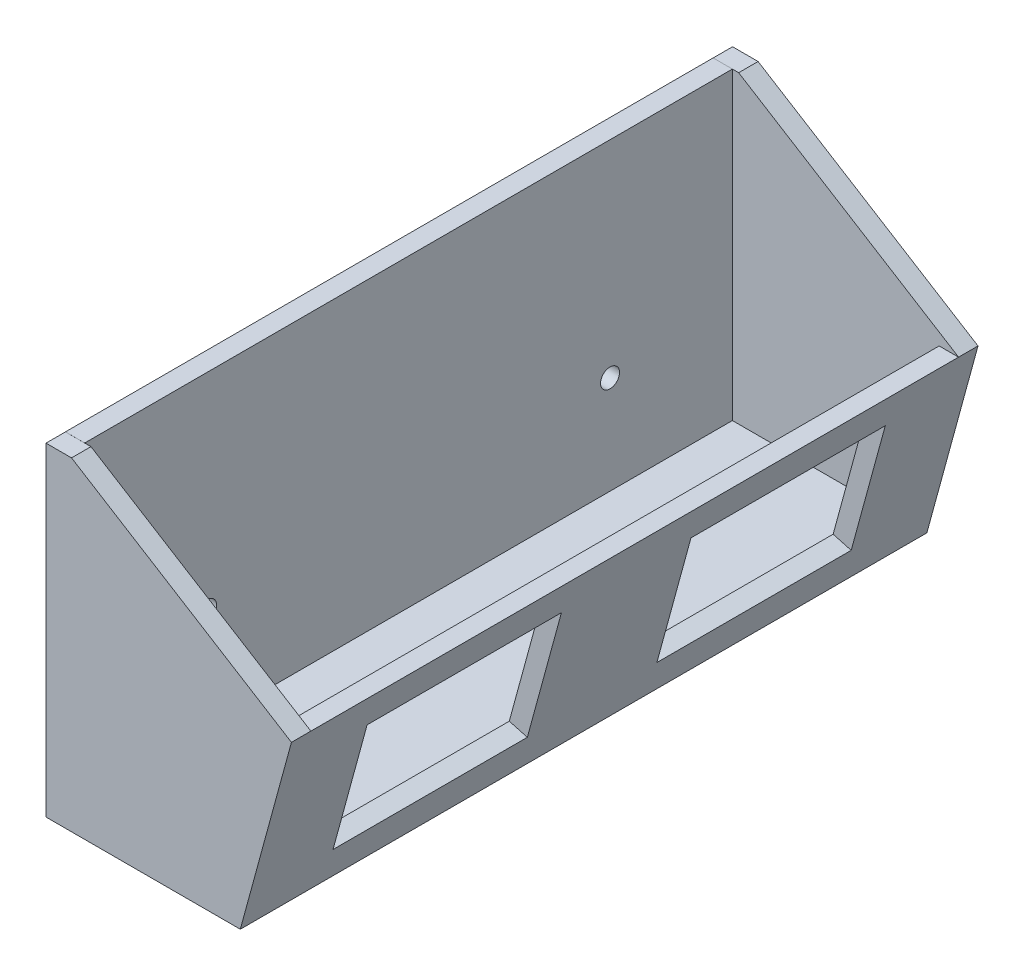
SolidWorks part; units mm, degrees
ref_plane "Front Plane" through (0, 0, 0) normal (0, 0, 1) x (1, 0, 0)
ref_plane "Top Plane" through (0, 0, 0) normal (0, 1, 0) x (1, 0, 0)
ref_plane "Right Plane" through (0, 0, 0) normal (1, 0, 0) x (0, 0, -1)
sketch "Esquisse2" plane through (0, 0, 0) normal (0, 0, 1) x (1, 0, 0)
  line L0 (0, 0) -> (0, 50)
  line L1 (0, 50) -> (3.9428, 50)
  line L2 (37.8943, 28.9427) -> (30, 0)
  line L3 (30, 0) -> (0, 0)
  line L4 (3.9428, 50) -> (37.8943, 28.9427)
  dimension "D1" = 50
  dimension "D2" = 30
  dimension "D3" = 30
  dimension "D4" = 105.257
extrude "Boss.-Extru.1" add sketch "Esquisse2" along normal blind 3
sketch "Esquisse4" plane through (0, 0, 3) normal (0, 0, 1) x (1, 0, 0)
  line L0 (0, 0) -> (0, 3.0061)
  line L1 (0, 50) -> (0, 0) construction
  line L2 (0, 3.0061) -> (30.8199, 3.0061)
  line L3 (30, 0) -> (37.8943, 28.9427) construction
  line L4 (30.8199, 3.0061) -> (30, 0)
  line L5 (30, 0) -> (0, 0)
extrude "Boss.-Extru.2" add sketch "Esquisse4" along normal blind 100
pattern_linear "Répétition linéaire1" count 2 spacing 103 along (0, 0, 1) of "Boss.-Extru.1"
sketch "Esquisse5" plane through (0, 3.0061, 0) normal (0, 1, 0) x (1, 0, 0)
  line L0 (30.8199, -103) -> (0, -103) construction
  line L1 (0, -3) -> (2.9757, -3)
  line L2 (0, -3) -> (0, -103)
  line L3 (0, -103) -> (2.9757, -103)
  line L4 (2.9757, -3) -> (2.9757, -103)
extrude "Boss.-Extru.3" add sketch "Esquisse5" along normal blind 47
sketch "Esquisse6" plane through (0, 3.0061, 0) normal (0, 1, 0) x (1, 0, 0)
  line L0 (30.8199, -103) -> (2.9757, -103) construction
  line L1 (30.8199, -3) -> (27.8243, -3)
  line L2 (30.8199, -3) -> (30.8199, -103)
  line L3 (30.8199, -103) -> (27.8243, -103)
  line L4 (27.8243, -3) -> (27.8243, -103)
sweep "Balayage1" add profiles "Esquisse6" path edge at (34.3571, 15.9744, 103)
sketch "Esquisse7" plane through (27.9227, -7.6161, 0) normal (0.9648, -0.2631, 0) x (0, 0, -1)
  line L0 (-53, 37.8943) -> (-53, 7.8943) construction
  line L1 (-93, 32.8943) -> (-63, 32.8943)
  line L2 (-93, 32.8943) -> (-93, 12.8943)
  line L3 (-93, 12.8943) -> (-63, 12.8943)
  line L4 (-63, 32.8943) -> (-63, 12.8943)
  line L5 (-103, 37.8943) -> (-3, 37.8943) construction
  line L6 (-106, 7.8943) -> (0, 7.8943) construction
  line L7 (-106, 22.8943) -> (0, 22.8943) construction
  line L8 (-106, 7.8943) -> (-106, 37.8943) construction
  line L9 (0, 7.8943) -> (0, 37.8943) construction
  point P16 (-93, 22.8943)
  dimension "D1" = 20
  dimension "D2" = 30
  dimension "D3" = 10
extrude "Enlèv. mat.-Extru.1" cut sketch "Esquisse7" against normal up to next
sketch "Esquisse8" plane through (27.9227, -7.6161, 0) normal (0.9648, -0.2631, 0) x (0, 0, -1)
  line L0 (-53, 37.8943) -> (-53, 7.8943) construction
  line L1 (-103, 37.8943) -> (-3, 37.8943) construction
  line L2 (-106, 7.8943) -> (0, 7.8943) construction
ref_plane "Plan3" through (0, 0, 53) normal (0, 0, 1) x (-0.2631, -0.9648, 0)
mirror "Symétrie1" about plane through (0, 0, 53) normal (0, 0, 1) of "Enlèv. mat.-Extru.1"
sketch "Esquisse9" plane through (2.9757, 0, 0) normal (1, 0, 0) x (0, 0, -1)
  circle A0 centre (-84.1079, 18.1575) radius 1.4621
  point P2 (-84.1079, 18.1575)
extrude "Enlèv. mat.-Extru.8" cut sketch "Esquisse9" against normal blind 10
mirror "Symétrie3" about plane through (0, 0, 53) normal (0, 0, 1) of "Enlèv. mat.-Extru.8"
